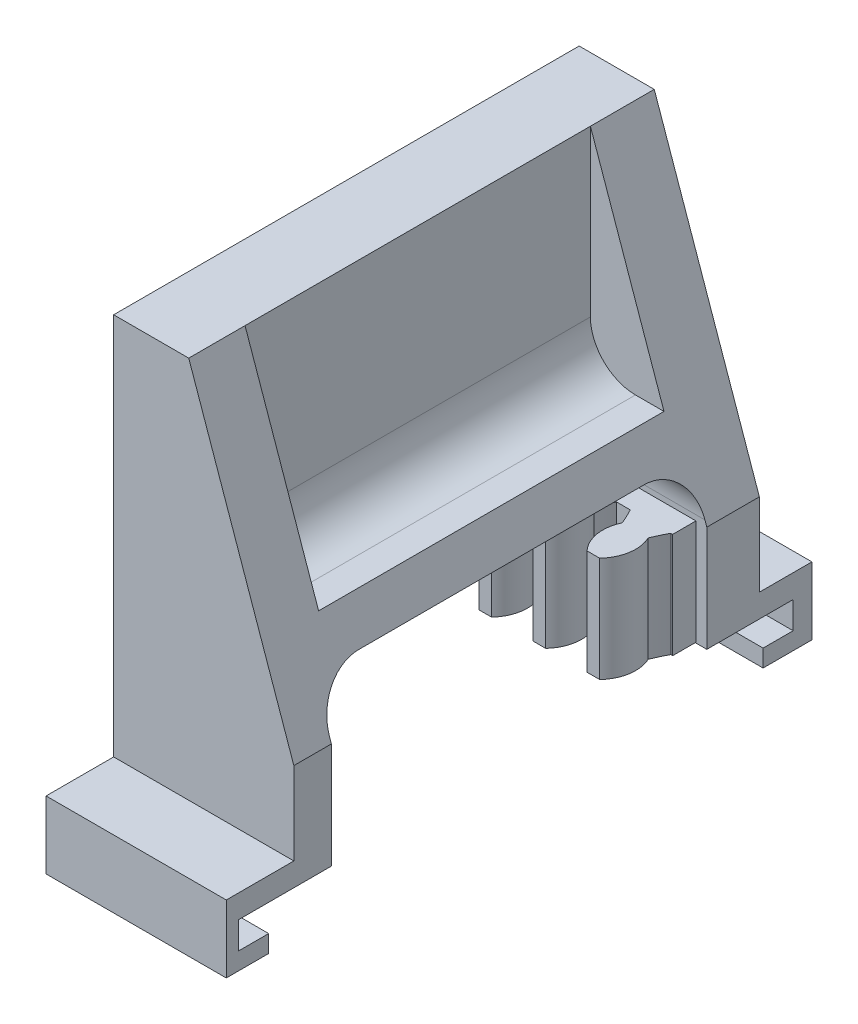
SolidWorks part; units mm, degrees
ref_plane "Front Plane" through (0, 0, 0) normal (0, 0, 1) x (1, 0, 0)
ref_plane "Top Plane" through (0, 0, 0) normal (0, 1, 0) x (1, 0, 0)
ref_plane "Right Plane" through (0, 0, 0) normal (1, 0, 0) x (0, 0, -1)
sketch "Sketch1" plane through (0, 0, 0) normal (0, 0, 1) x (1, 0, 0)
  line L0 (0, 0) -> (0, -30)
  line L1 (0, -30) -> (12, -30)
  line L2 (12, -30) -> (12, -20)
  line L3 (12, -20) -> (5, 0)
  line L4 (5, 0) -> (0, 0)
  dimension "D1" = 30
  dimension "D2" = 12
  dimension "D3" = 10
  dimension "D4" = 5
extrude "Boss-Extrude1" add sketch "Sketch1" against normal blind 31
sketch "Sketch4" plane through (0, 0, 0) normal (-1, 0, 0) x (0, 0, 1)
  line L0 (-31, 0) -> (-31, -30) construction
  line L1 (-27.5, -16.6434) -> (-2.5, -16.6434)
  line L2 (-27.5, -16.6434) -> (-27.5, -31.6434)
  line L3 (-27.5, -31.6434) -> (-2.5, -31.6434)
  line L4 (-2.5, -16.6434) -> (-2.5, -31.6434)
  point P4 (-27.5, -24.1434)
  dimension "D1" = 25
  dimension "D2" = 15
  dimension "D3" = 3.5
extrude "Cut-Extrude2" cut sketch "Sketch4" against normal blind 25 contours L2 L1 L4 L3
ref_plane "Plane1" through (0, 0, -15.25) normal (0, 0, 1) x (1, 0, 0)
sketch "Sketch6" plane through (0, 0, -15.25) normal (0, 0, 1) x (1, 0, 0)
  line L0 (5, 0) -> (5, -14)
  line L1 (5, -14) -> (9.9, -14)
  line L2 (12, -20) -> (5, 0) construction
  line L3 (9.9, -14) -> (5, 0)
  dimension "D1" = 14
extrude "Cut-Extrude4" cut sketch "Sketch6" against normal mid plane 23
ref_plane "Plane3" through (0, -27, 0) normal (0, 1, 0) x (1, 0, 0)
sketch "Sketch7" plane through (0, -27, 0) normal (0, 1, 0) x (1, 0, 0)
  line L0 (11.2768, 27.65) -> (-19.7232, 27.65)
  line L62 (-16.5, 15.25) -> (16.5, 15.25) construction
  line L162 (11.2768, 27.65) -> (11.2768, 25.95)
  line L172 (-19.7232, 25.95) -> (-19.7232, 27.65)
  line L243 (11.2768, 25.95) -> (-19.7232, 25.95)
  dimension "D2" = 31
  dimension "D3" = 1.7
  dimension "D7" = 12.4
extrude "Boss-Extrude3" add sketch "Sketch7" along normal blind 7
sketch "Sketch10" plane through (0, -27, 0) normal (0, 1, 0) x (1, 0, 0)
  line L1 (9.8022, 22.1441) -> (9.8022, 23.4692) construction
  line L2 (10.2262, 22.1441) -> (9.3781, 22.1441)
  line L4 (-19.7232, 25.95) -> (11.2768, 25.95) construction
  line L5 (8.4522, 25.95) -> (11.1522, 25.95)
  arc A0 (10.2262, 22.1441) -> (10.6705, 24.929) centre (8.3868, 23.8654) ccw
  arc A1 (10.6705, 24.929) -> (11.1522, 25.95) centre (19.5896, 21.3459) cw
  arc A2 (8.9338, 24.929) -> (8.4522, 25.95) centre (0.0147, 21.3459) ccw
  arc A3 (9.3781, 22.1441) -> (8.9338, 24.929) centre (11.2175, 23.8654) cw
  point P7 (8.4522, 25.25)
  point P15 (10.2262, 22.1441)
  dimension "D1" = 2.7
extrude "Boss-Extrude4" add sketch "Sketch10" along normal blind 7
pattern_linear "LPattern1" count 8 spacing 3.6 along (-1, 0, 0) of "Boss-Extrude4"
sketch "Sketch11" plane through (0, 0, -31) normal (0, 0, -1) x (-1, 0, 0)
  line L0 (-12, -30) -> (-12, -20) construction
  line L1 (-12, -25.5) -> (0, -25.5)
  line L2 (-12, -25.5) -> (-12, -30)
  line L3 (-12, -30) -> (0, -30)
  line L4 (0, -25.5) -> (0, -30)
  dimension "D1" = 4.5
extrude "Boss-Extrude5" add sketch "Sketch11" along normal blind 3.5
fillet "Fillet5" radius 3 3 edges at (5, -14, -15.25) (5.4126, -16.6434, -2.5) (5.4126, -16.6434, -27.5)
sketch "Sketch12" plane through (0, 0, 0) normal (0, 0, 1) x (1, 0, 0)
  line L0 (12, -30) -> (12, -20) construction
  line L1 (0, -30) -> (12, -30)
  line L2 (0, -30) -> (0, -25.5)
  line L3 (0, -25.5) -> (12, -25.5)
  line L4 (12, -30) -> (12, -25.5)
  dimension "D1" = 4.5
extrude "Boss-Extrude6" add sketch "Sketch12" along normal blind 4.5
sketch "Sketch13" plane through (0, 0, 0) normal (-1, 0, 0) x (0, 0, 1)
  line L0 (-33.25, -27.0479) -> (-26.75, -27.0479)
  line L1 (-26.75, -27.0479) -> (-26.75, -32.0479)
  line L2 (-26.75, -32.0479) -> (-31.25, -32.0479)
  line L3 (-31.25, -32.0479) -> (-31.25, -28.8479)
  line L4 (-31.25, -28.8479) -> (-33.25, -28.8479)
  line L5 (-33.25, -28.8479) -> (-33.25, -27.0479)
  line L6 (-14.7869, -22.9316) -> (-14.7869, -37.9805) construction
  line L9 (-27.5, -27) -> (-27.5, -30) construction
  line L12 (1.6762, -28.8479) -> (3.6762, -28.8479)
  line L13 (1.6762, -32.0479) -> (1.6762, -28.8479)
  line L14 (-2.8238, -32.0479) -> (1.6762, -32.0479)
  line L15 (-2.8238, -27.0479) -> (-2.8238, -32.0479)
  line L16 (3.6762, -27.0479) -> (-2.8238, -27.0479)
  line L17 (3.6762, -28.8479) -> (3.6762, -27.0479)
  point P20 (-15.5, -22.9316)
  point P21 (0, 0)
  dimension "D1" = 6.5
  dimension "D2" = 0.75
  dimension "D3" = 4.5
  dimension "D4" = 1.8
extrude "Cut-Extrude5" cut sketch "Sketch13" against normal up to surface (12 mm away) up to face at (12, -25.1667, -31)
